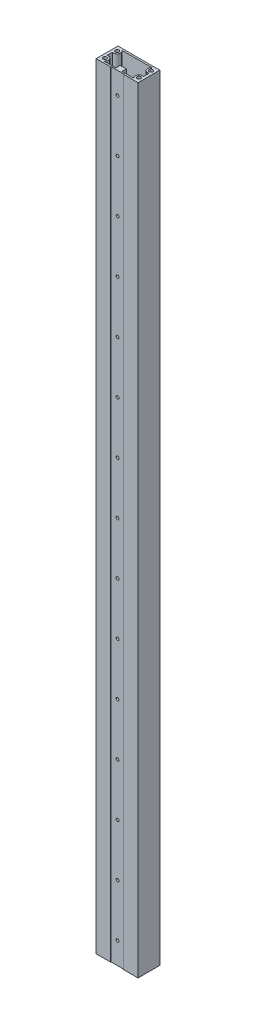
SolidWorks part; units mm, degrees
ref_plane "前视基准面" through (0, 0, 0) normal (0, 0, 1) x (1, 0, 0)
ref_plane "上视基准面" through (0, 0, 0) normal (0, 1, 0) x (1, 0, 0)
ref_plane "右视基准面" through (0, 0, 0) normal (1, 0, 0) x (0, 0, -1)
sketch "草图1" plane through (0, 0, 0) normal (0, 1, 0) x (1, 0, 0)
  line L0 (0, 0) -> (0, 49.4431) construction
  line L1 (-24, 12.5) -> (24, 12.5)
  line L2 (-24, 12.5) -> (-24, -12.5)
  line L3 (-24, -12.5) -> (24, -12.5)
  line L4 (24, 12.5) -> (24, -12.5)
  line L5 (0, 0) -> (72.6583, 0) construction
  dimension "D1" = 48
  dimension "D2" = 25
extrude "凸台-拉伸1" add sketch "草图1" along normal mid plane 890
sketch "草图2" plane through (0, -445, 0) normal (0, -1, 0) x (1, 0, 0)
  line L0 (0, 0) -> (-29.7097, 0) construction
  line L1 (0, 0) -> (0, 17.5508) construction
  line L3 (-17.5635, 10.5) -> (-3.5, 10.5)
  line L4 (-17.5635, -10.5) -> (17.5635, -10.5)
  line L5 (-21, 3.2919) -> (-21, -3.2919)
  line L6 (21, 3.2919) -> (21, -3.2919)
  line L7 (-3.5, 10.5) -> (-3.5, 5.5)
  line L8 (-3.5, 5.5) -> (3.5, 5.5)
  line L9 (3.5, 5.5) -> (3.5, 10.5)
  line L10 (3.5, 10.5) -> (17.5635, 10.5)
  circle A0 centre (-19.5, 7) radius 1.9
  circle A1 centre (-19.5, -7) radius 1.9
  circle A2 centre (19.5, -7) radius 1.9
  circle A3 centre (19.5, 7) radius 1.9
  arc A4 (-21, 3.2919) -> (-17.5635, 10.5) centre (-19.5, 7) ccw
  arc A5 (21, 3.2919) -> (17.5635, 10.5) centre (19.5, 7) cw
  arc A6 (21, -3.2919) -> (17.5635, -10.5) centre (19.5, -7) ccw
  arc A7 (-21, -3.2919) -> (-17.5635, -10.5) centre (-19.5, -7) cw
  dimension "D3" = 3.8
  dimension "D6" = 4
  dimension "D1" = 39
  dimension "D2" = 14
  dimension "D4" = 42
  dimension "D5" = 21
  dimension "D7" = 7
  dimension "D8" = 5
extrude "切除-拉伸1" cut sketch "草图2" against normal through all
sketch "草图3" plane through (0, -445, 0) normal (0, -1, 0) x (1, 0, 0)
  line L0 (-24, 12.5) -> (24, 12.5) construction
  line L1 (-7.5, 12.5) -> (7.5, 12.5)
  line L2 (-7.5, 12.5) -> (-7.5, 12)
  line L3 (-7.5, 12) -> (7.5, 12)
  line L4 (7.5, 12.5) -> (7.5, 12)
  line L5 (0, 0) -> (0, 14.6656) construction
  dimension "D1" = 15
  dimension "D2" = 0.5
extrude "切除-拉伸2" cut sketch "草图3" against normal through all
hole_wizard "M4x0.7 螺纹孔1" positions "草图5" profile "草图4" tap size "M4x0.7" standard "JIS"
sketch "草图5" plane through (0, 0, 12) normal (0, 0, 1) x (1, 0, 0)
  line L0 (0, 445) -> (0, 420) construction
  line L1 (-7.5, 445) -> (7.5, 445) construction
  point P1 (0, 420)
  dimension "D1" = 25
sketch "草图4" plane through (0, 420, 12) normal (1, 0, 0) x (0, -1, 0)
  line L0 (0, 0) -> (0, 11.0914)
  line L1 (0, 11.0914) -> (1.65, 10.1)
  line L2 (1.65, 10.1) -> (1.65, 0)
  line L5 (1.65, 0) -> (0, 0)
  line L10 (0, 11.0914) -> (-1.65, 10.1) construction
  line L11 (0, -6.35) -> (0, 107.95) construction
  dimension "螺纹孔钻头直径" = 3.3
  dimension "螺纹孔钻头深度" = 10.1
  dimension "导头角度" = 118
cosmetic thread "孔螺蚊线1" parameters "D1"=6.8, "D2"=4
pattern_linear "阵列(线性)1" count 15 spacing 60 along (0, -1, 0) of "M4x0.7 螺纹孔1"
sketch "草图6" plane through (0, 0, -12.5) normal (0, 0, -1) x (-1, 0, 0)
  line L0 (0, -400) -> (0, -445) construction
  line L1 (-24, -445) -> (24, -445) construction
  line L2 (10, -400) -> (10, -445)
  line L3 (-10, -400) -> (-10, -445)
  arc A0 (10, -400) -> (-10, -400) centre (0, -400) ccw
  arc A1 (-10, -445) -> (10, -445) centre (0, -445) ccw
  point P4 (0, -422.5)
  dimension "D1" = 10
  dimension "D2" = 45
extrude "切除-拉伸3" cut sketch "草图6" against normal up to surface (2 mm away) up to face at (0, 0, -10.5)
hole_wizard "M5x0.8 螺纹孔1" positions "草图8" profile "草图7" tap size "M5x0.8" standard "JIS"
sketch "草图8" plane through (0, 445, 0) normal (0, 1, 0) x (-1, 0, 0)
  point P1 (19.5, -7)
  point P4 (19.5, 7)
  point P7 (-19.5, -7)
  point P10 (-19.5, 7)
sketch "草图7" plane through (-19.5, 445, -7) normal (1, 0, 0) x (0, 0, 1)
  line L0 (0, 0) -> (0, 13.6618)
  line L1 (0, 13.6618) -> (2.1, 12.4)
  line L2 (2.1, 12.4) -> (2.1, 0)
  line L5 (2.1, 0) -> (0, 0)
  line L10 (0, 13.6618) -> (-2.1, 12.4) construction
  line L11 (0, -6.35) -> (0, 107.95) construction
  dimension "螺纹孔钻头直径" = 4.2
  dimension "螺纹孔钻头深度" = 12.4
  dimension "导头角度" = 118
cosmetic thread "孔螺蚊线2" parameters "D1"=10, "D2"=5
cosmetic thread "孔螺蚊线3" parameters "D1"=10, "D2"=5
cosmetic thread "孔螺蚊线4" parameters "D1"=10, "D2"=5
cosmetic thread "孔螺蚊线5" parameters "D1"=10, "D2"=5
mirror "镜向1" about plane through (0, 0, 0) normal (0, 1, 0) of "M5x0.8 螺纹孔1"
